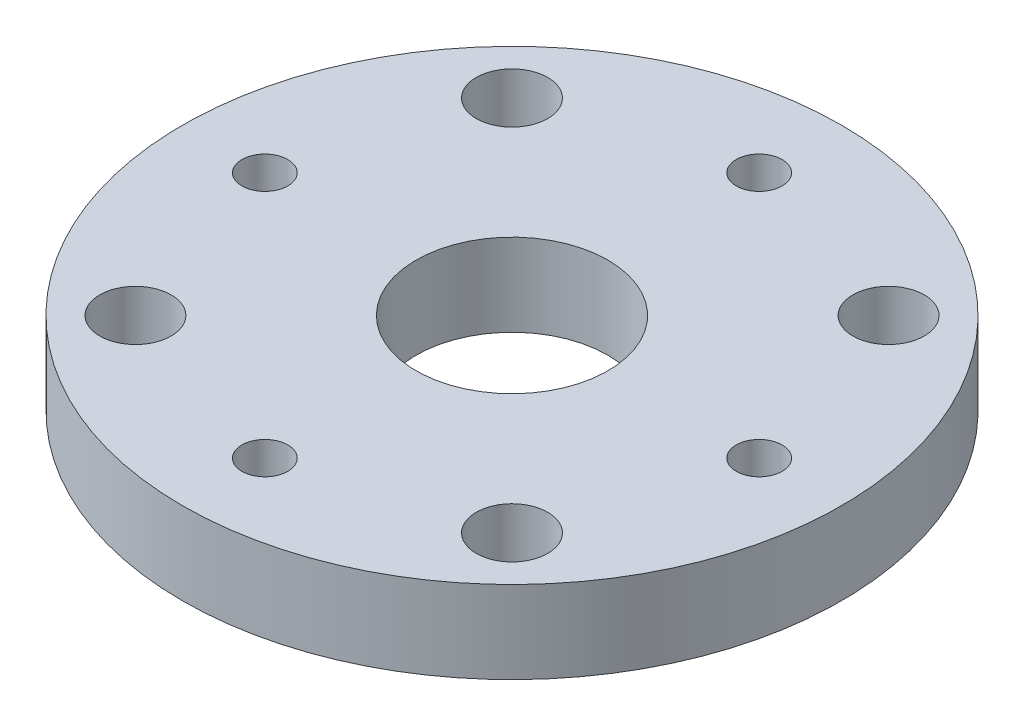
SolidWorks part; units mm, degrees
ref_plane "Front Plane" through (0, 0, 0) normal (0, 0, 1) x (1, 0, 0)
ref_plane "Top Plane" through (0, 0, 0) normal (0, 1, 0) x (1, 0, 0)
ref_plane "Right Plane" through (0, 0, 0) normal (1, 0, 0) x (0, 0, -1)
sketch "Sketch1" plane through (0, 0, 0) normal (0, 1, 0) x (1, 0, 0)
  circle A0 centre (0, 0) radius 60
  dimension "D1" = 120
extrude "Boss-Extrude1" add sketch "Sketch1" along normal blind 15
sketch "Sketch2" plane through (0, 15, 0) normal (0, 1, 0) x (1, 0, 0)
  circle A0 centre (45, 0) radius 4.175
  circle A1 centre (0, -45) radius 4.175
  circle A2 centre (-45, 0) radius 4.175
  circle A3 centre (0, 45) radius 4.175
  dimension "D1" = 8.35
  dimension "D2" = 45
  dimension "D3" = 4
extrude "Cut-Extrude1" cut sketch "Sketch2" against normal blind 10
sketch "Sketch3" plane through (0, 0, 0) normal (0, -1, 0) x (1, 0, 0)
  line L0 (-60, 0) -> (60, 0) construction
  line L1 (0, 60) -> (0, -60) construction
  line L2 (34.2805, -34.2805) -> (0, 0) construction
  line L3 (0, 0) -> (-34.2805, 34.2805) construction
  circle A0 centre (34.2805, -34.2805) radius 2.75
  circle A1 centre (0, 0) radius 60 construction
  circle A2 centre (-34.2805, -34.2805) radius 2.75
  circle A3 centre (-34.2805, 34.2805) radius 2.75
  circle A4 centre (34.2805, 34.2805) radius 2.75
  dimension "D1" = 5.5
  dimension "D2" = 48.48
  dimension "D3" = 45
  dimension "D4" = 4
extrude "Cut-Extrude2" cut sketch "Sketch3" against normal through all
sketch "Sketch4" plane through (0, 0, 0) normal (0, -1, 0) x (1, 0, 0)
  circle A0 centre (0, 0) radius 17.4625
  dimension "D1" = 34.925
extrude "Cut-Extrude3" cut sketch "Sketch4" against normal through all
sketch "Sketch5" plane through (0, 15, 0) normal (0, 1, 0) x (1, 0, 0)
  line L0 (-34.2805, 34.2805) -> (0, 0) construction
  line L1 (0, 0) -> (34.2805, -34.2805) construction
  circle A0 centre (-34.2805, 34.2805) radius 6.5
  circle A1 centre (34.2805, 34.2805) radius 6.5
  circle A2 centre (34.2805, -34.2805) radius 6.5
  circle A3 centre (-34.2805, -34.2805) radius 6.5
  dimension "D1" = 13
  dimension "D2" = 4
extrude "Cut-Extrude4" cut sketch "Sketch5" against normal offset from surface (10 mm away) 5 up to face at (0, 0, -17.4625)
